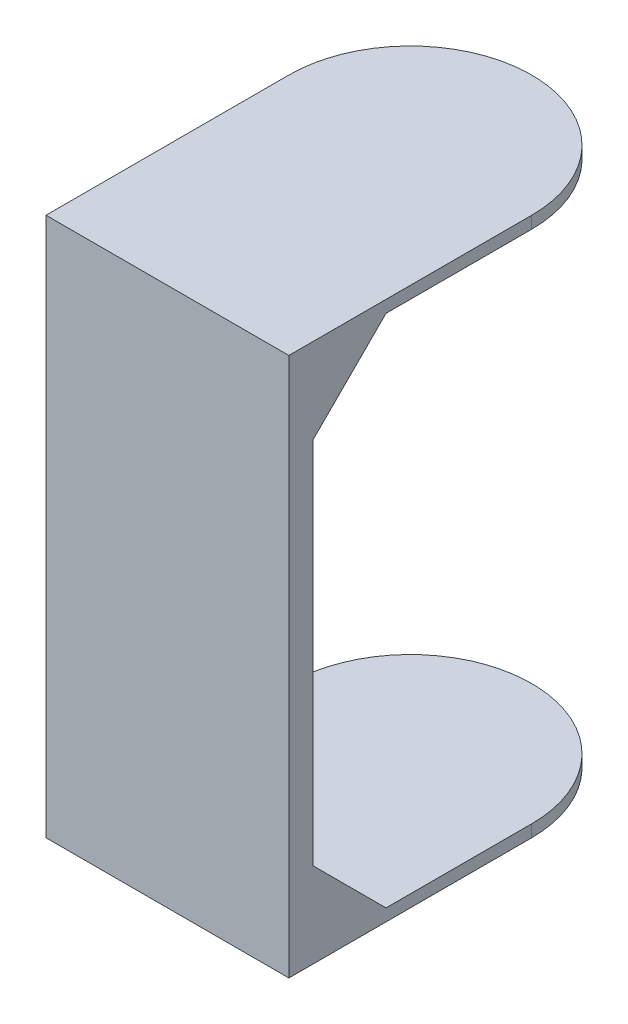
SolidWorks part; units mm, degrees
ref_plane "Front Plane" through (0, 0, 0) normal (0, 0, 1) x (1, 0, 0)
ref_plane "Top Plane" through (0, 0, 0) normal (0, 1, 0) x (1, 0, 0)
ref_plane "Right Plane" through (0, 0, 0) normal (1, 0, 0) x (0, 0, -1)
sketch "Plate Sketch" plane through (0, 0, 0) normal (0, 0, 1) x (1, 0, 0)
  line L1 (-50, 106) -> (50, 106)
  line L2 (-50, 106) -> (-50, -106)
  line L3 (-50, -106) -> (50, -106)
  line L4 (50, 106) -> (50, -106)
  line L5 (-50, 106) -> (50, -106) construction
  line L6 (-50, -106) -> (50, 106) construction
  point P0 (0, 0)
  dimension "D1" = 100
  dimension "D2" = 212
extrude "Plate Extrude" add sketch "Plate Sketch" against normal blind 10
sketch "Primary Support Sketch" plane through (50, 0, 0) normal (1, 0, 0) x (0, 0, -1)
  line L0 (10, 106) -> (10, 76)
  line L1 (10, 76) -> (40, 106)
  line L2 (40, 106) -> (10, 106)
  dimension "D1" = 30
extrude "Primary Support Extrude" add sketch "Primary Support Sketch" against normal blind 10
mirror "Primary Support Mirror" about plane through (0, 0, 0) normal (0, 1, 0) of "Primary Support Extrude"
sketch "Secondary Support Sketch" plane through (-50, 0, 0) normal (-1, 0, 0) x (0, 0, 1)
  line L0 (-10, -76) -> (-40, -106)
  line L1 (-10, 106) -> (-10, -106) construction
  line L2 (-10, -106) -> (-10, -76) construction
  line L3 (-40, -106) -> (-10, -106)
  line L4 (-10, -106) -> (-10, -76)
extrude "Secondary Support Extrude" add sketch "Secondary Support Sketch" against normal blind 10
sketch "Gripper Sketch" plane through (0, 106, 0) normal (0, 1, 0) x (1, 0, 0)
  line L0 (50, 100) -> (-50, 100) construction
  line L1 (0, 150) -> (0, 0) construction
  line L7 (-50, 0) -> (50, 0)
  line L8 (-50, 0) -> (-50, 100)
  line L9 (-50, 100) -> (50, 100) construction
  line L10 (50, 0) -> (50, 100)
  line L11 (-50, 0) -> (50, 100) construction
  line L12 (-50, 100) -> (50, 0) construction
  arc A0 (50, 100) -> (-50, 100) centre (0, 100) ccw
  point P5 (0, 150)
  point P6 (0, 50)
extrude "Gripper Extrude" add sketch "Gripper Sketch" along normal blind 5
mirror "Gripper Mirror" about plane through (0, 0, 0) normal (0, 1, 0) of "Gripper Extrude"
